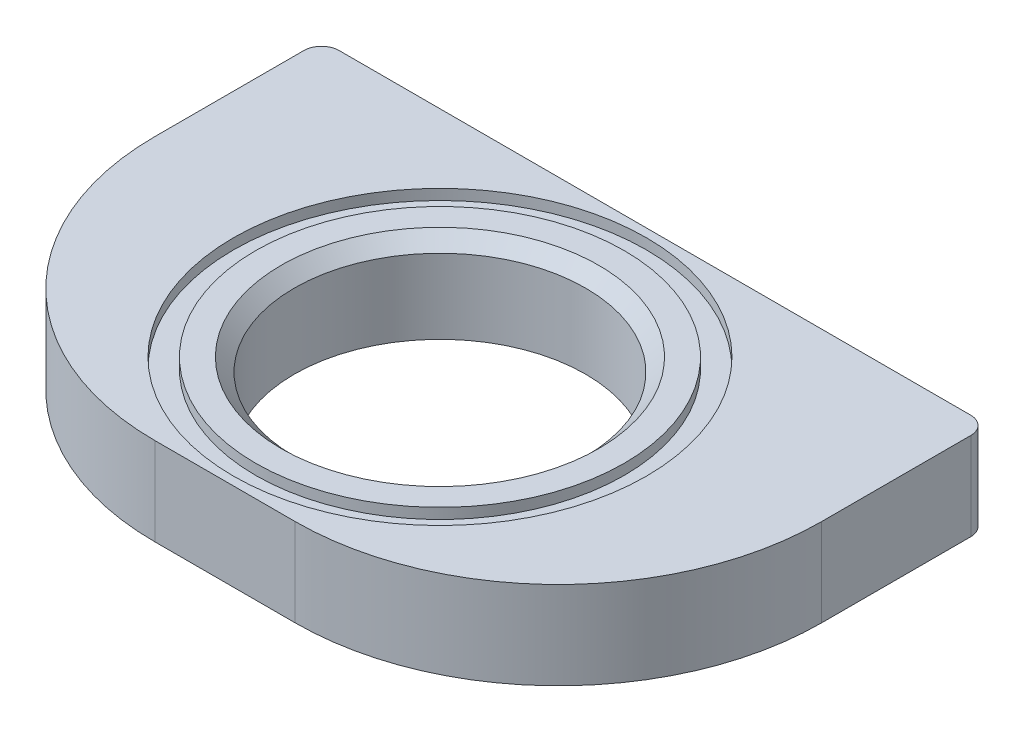
SolidWorks part; units mm, degrees
ref_plane "Front Plane" through (0, 0, 0) normal (0, 0, 1) x (1, 0, 0)
ref_plane "Top Plane" through (0, 0, 0) normal (0, 1, 0) x (1, 0, 0)
ref_plane "Right Plane" through (0, 0, 0) normal (1, 0, 0) x (0, 0, -1)
sketch "Sketch1" plane through (0, 0, 0) normal (0, 1, 0) x (1, 0, 0)
  line L1 (-19, 12.25) -> (19, 12.25)
  line L2 (-19, 12.25) -> (-19, -12.25)
  line L3 (-19, -12.25) -> (19, -12.25)
  line L4 (19, 12.25) -> (19, -12.25)
  circle A0 centre (0, 0) radius 8.3
  dimension "D5" = 16.6
  dimension "D1" = 38
  dimension "D2" = 24.5
  dimension "D3" = 12.25
  dimension "D4" = 19
extrude "Boss-Extrude1" add sketch "Sketch1" along normal blind 5
fillet "Fillet1" radius 15 2 edges at (19, 2.5, 12.25) (-19, 2.5, 12.25)
fillet "Fillet2" radius 1 2 edges at (-19, 2.5, -12.25) (19, 2.5, -12.25)
chamfer "Chamfer1" distance 0.75 angle 45 1 edges at (0, 5, 8.3)
sketch "Sketch2" plane through (0, 5, 0) normal (0, 1, 0) x (1, 0, 0)
  circle A0 centre (0, 0) radius 10.8807
sketch "Sketch3" plane through (0, 0, 0) normal (0, 0, 1) x (1, 0, 0)
  line L0 (18, 5) -> (-18, 5) construction
  line L1 (-10.5, 5.5513) -> (-11.7671, 5.5513)
  line L2 (-10.5, 5.5513) -> (-10.5, 4.4)
  line L3 (-10.5, 4.4) -> (-11.7671, 4.4)
  line L4 (-11.7671, 5.5513) -> (-11.7671, 4.4)
  dimension "D1" = 10.5
  dimension "D2" = 0.6
sketch "Sketch4" plane through (0, 5, 0) normal (0, 1, 0) x (1, 0, 0)
  circle A0 centre (0, 0) radius 11
sweep "o-ring" cut profiles "Sketch3" path "Sketch4"
